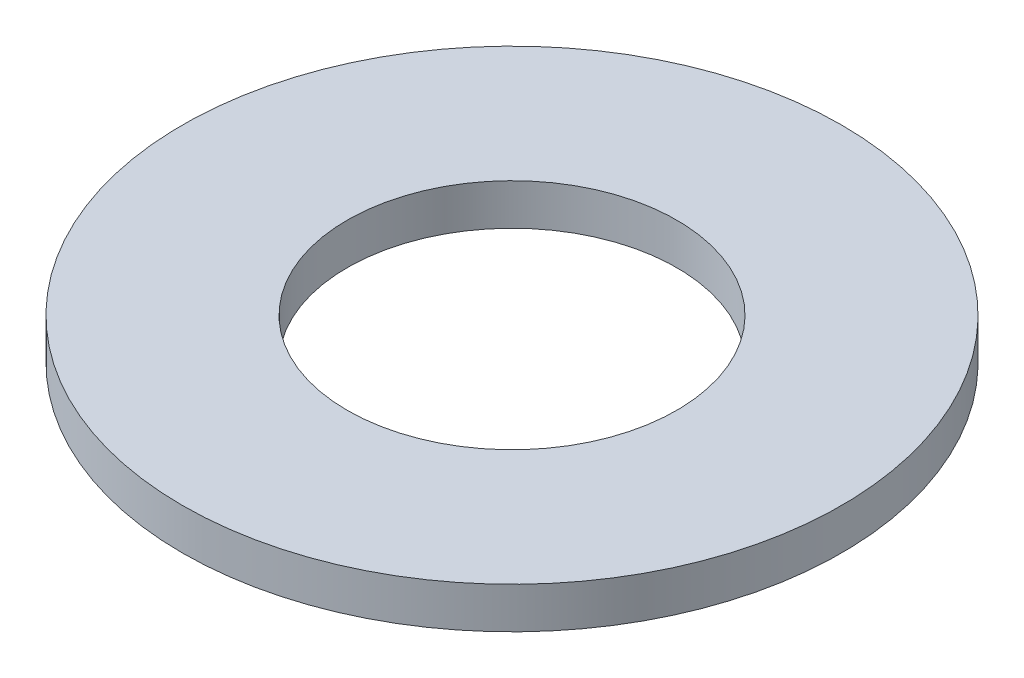
SolidWorks part; units mm, degrees
material "AISI 321 Annealed Stainless Steel (SS)"
ref_plane "Front Plane" through (0, 0, 0) normal (0, 0, 1) x (1, 0, 0)
ref_plane "Top Plane" through (0, 0, 0) normal (0, 1, 0) x (1, 0, 0)
ref_plane "Right Plane" through (0, 0, 0) normal (1, 0, 0) x (0, 0, -1)
sketch "Sketch1" plane through (0, 0, 0) normal (0, 1, 0) x (1, 0, 0)
  circle A0 centre (0, 0) radius 1
  circle A1 centre (0, 0) radius 2
  dimension "D1" = 2
  dimension "D2" = 4
extrude "Boss-Extrude1" add sketch "Sketch1" along normal blind 0.25
